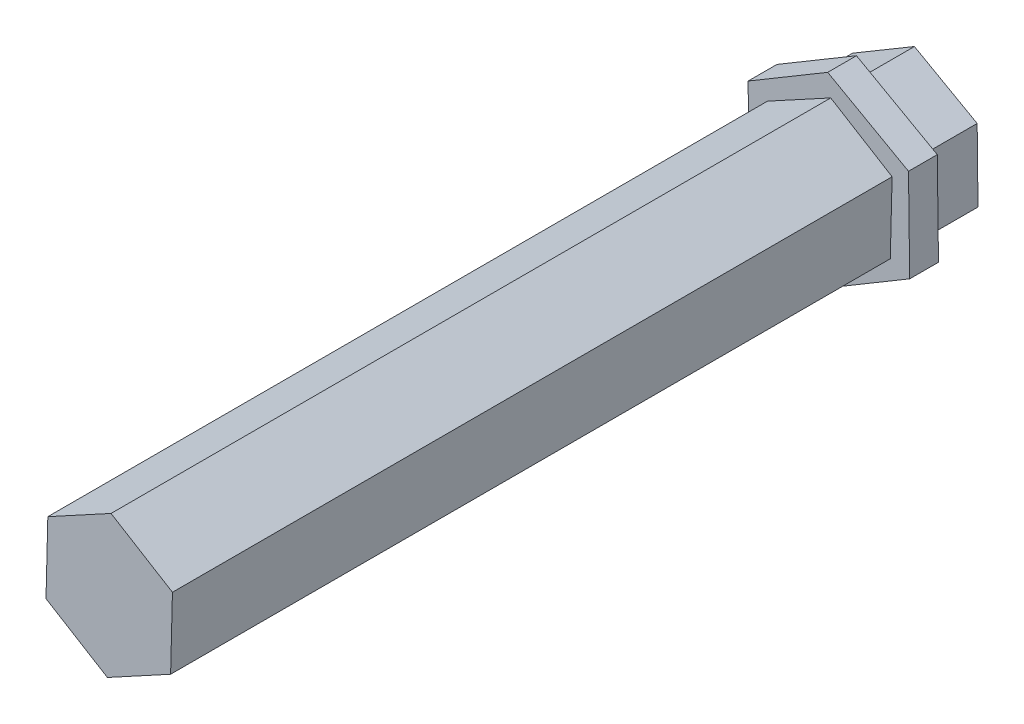
SolidWorks part; units mm, degrees
ref_plane "Front Plane" through (0, 0, 0) normal (0, 0, 1) x (1, 0, 0)
ref_plane "Top Plane" through (0, 0, 0) normal (0, 1, 0) x (1, 0, 0)
ref_plane "Right Plane" through (0, 0, 0) normal (1, 0, 0) x (0, 0, -1)
sketch "Sketch2" plane through (0, 0, 0) normal (0, 0, 1) x (1, 0, 0)
  line L1 (2.1327, -1.3045) -> (2.196, 1.1947)
  line L2 (2.196, 1.1947) -> (0.0634, 2.4992)
  line L3 (0.0634, 2.4992) -> (-2.1327, 1.3045)
  line L4 (-2.1327, 1.3045) -> (-2.196, -1.1947)
  line L5 (-2.196, -1.1947) -> (-0.0634, -2.4992)
  line L6 (-0.0634, -2.4992) -> (2.1327, -1.3045)
  circle A0 centre (0, 0) radius 2.1651 construction
  dimension "D1" = 2.5
extrude "Boss-Extrude1" add sketch "Sketch2" along normal blind 25
sketch "Sketch3" plane through (0, 0, 0) normal (0, 0, 1) x (1, 0, 0)
  line L1 (2.8067, -1.5724) -> (2.7651, 1.6444)
  line L2 (2.7651, 1.6444) -> (-0.0416, 3.2169)
  line L3 (-0.0416, 3.2169) -> (-2.8067, 1.5724)
  line L4 (-2.8067, 1.5724) -> (-2.7651, -1.6444)
  line L5 (-2.7651, -1.6444) -> (0.0416, -3.2169)
  line L6 (0.0416, -3.2169) -> (2.8067, -1.5724)
  circle A0 centre (0, 0) radius 2.7861 construction
extrude "Boss-Extrude2" add sketch "Sketch3" against normal blind 1
sketch "Sketch4" plane through (0, 0, 0) normal (0, 0, 1) x (1, 0, 0)
  line L1 (-2.1504, -1.2751) -> (0.0291, -2.4998)
  line L2 (0.0291, -2.4998) -> (2.1794, -1.2247)
  line L3 (2.1794, -1.2247) -> (2.1504, 1.2751)
  line L4 (2.1504, 1.2751) -> (-0.0291, 2.4998)
  line L5 (-0.0291, 2.4998) -> (-2.1794, 1.2247)
  line L6 (-2.1794, 1.2247) -> (-2.1504, -1.2751)
  circle A0 centre (0, 0) radius 2.1651 construction
  dimension "D1" = 2.5
extrude "Boss-Extrude3" add sketch "Sketch4" against normal blind 3 contours L1 L2 L3 L4 L5 L6
